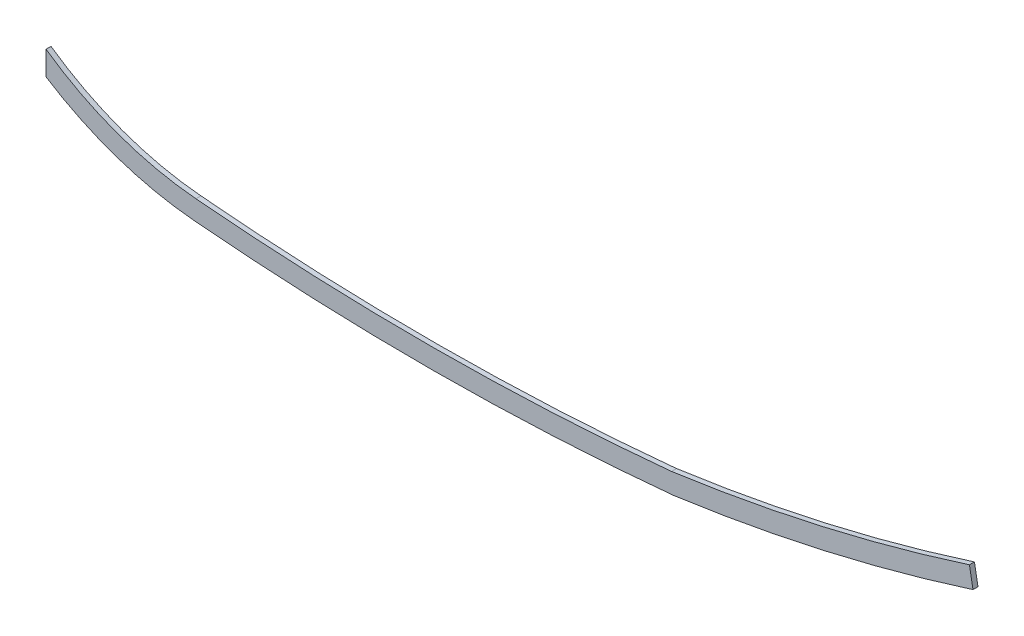
SolidWorks part; units mm, degrees
material "Balsa"
ref_plane "Front Plane" through (0, 0, 0) normal (0, 0, 1) x (1, 0, 0)
ref_plane "Top Plane" through (0, 0, 0) normal (0, 1, 0) x (1, 0, 0)
ref_plane "Right Plane" through (0, 0, 0) normal (1, 0, 0) x (0, 0, -1)
sketch "Sketch2" plane through (0, 0, 0) normal (0, 0, 1) x (1, 0, 0)
  line L0 (0, -93.726) -> (0, -78.486)
  line L2 (93.98, 0) -> (93.98, -379.755) construction
  line L3 (398.3737, -110.9898) -> (402.5381, -142.3403) construction
  line L4 (398.3737, -110.9898) -> (366.1948, 131.2634) construction
  line L5 (95.5675, -126.4975) -> (95.5675, 137.6625) construction
  line L7 (590.8643, -81.3536) -> (588.579, -68.7797)
  line L8 (0, 0) -> (672.417, 0) construction
  arc A0 (0, -93.726) -> (93.98, -125.8052) centre (112.6352, 82.55) ccw
  arc A1 (93.98, -125.8052) -> (400.2036, -124.7658) centre (241.5116, 1518.5899) ccw
  arc A2 (400.2036, -124.7658) -> (590.8643, -81.3536) centre (242.7057, 1007.3312) ccw
  arc A3 (95.6211, -113.2301) -> (398.7207, -112.1786) centre (241.5116, 1518.5899) ccw construction
  arc A4 (95.5675, -113.2253) -> (398.7207, -112.1786) centre (241.5116, 1518.5899) ccw
  arc A5 (398.7207, -112.1786) -> (588.579, -68.7797) centre (242.7057, 1007.3312) ccw
  arc A6 (94.4927, -125.8512) -> (400.2036, -124.7658) centre (241.5116, 1518.5899) ccw construction
  arc A7 (398.7207, -112.1786) -> (587.0046, -69.2844) centre (242.7057, 1007.3312) ccw construction
  arc A8 (0, -78.486) -> (95.5675, -113.2253) centre (112.6352, 82.55) ccw
  spline S0 degree 3 poles (3.7499, -94.8626) (10.597, -99.2271) (17.6385, -103.1401) (32.0968, -110.0953) (39.5136, -113.1375) (50.922, -117.0433) (54.7721, -118.2354) (60.6197, -119.8556) (62.5829, -120.3681) (66.5243, -121.3341) (68.5001, -121.787) (78.4043, -123.9021) (86.408, -125.1172) (94.4926, -125.8525) knots 0 0 0 0 0.25 0.25 0.5 0.5 0.625 0.625 0.6875 0.6875 0.75 0.75 1 1 1 1 construction
  spline S1 degree 3 poles (94.4926, -125.8525) (120.9278, -128.4258) (173.8258, -132.179) (226.7788, -133.168) (266.5142, -132.8729) (279.7628, -132.6016) (299.6408, -131.9345) (306.2677, -131.6688) (319.5231, -131.0505) (326.1536, -130.6977) (359.2877, -128.7173) (385.6949, -126.4433) (412.003, -123.4859) knots 0 0 0 0 0.25 0.5 0.5 0.625 0.625 0.6875 0.6875 0.75 0.75 1 1 1 1 construction
  point P24 (95.5727, -113.2253)
  point P29 (94.0152, -125.8085)
  dimension "D3" = 82.55
  dimension "D4" = 1651
  dimension "D5" = 1143
  dimension "D6" = 79.699
  dimension "D1" = 15.24
  dimension "D2" = 93.726
extrude "Boss-Extrude1" add sketch "Sketch2" along normal mid plane 3.175
